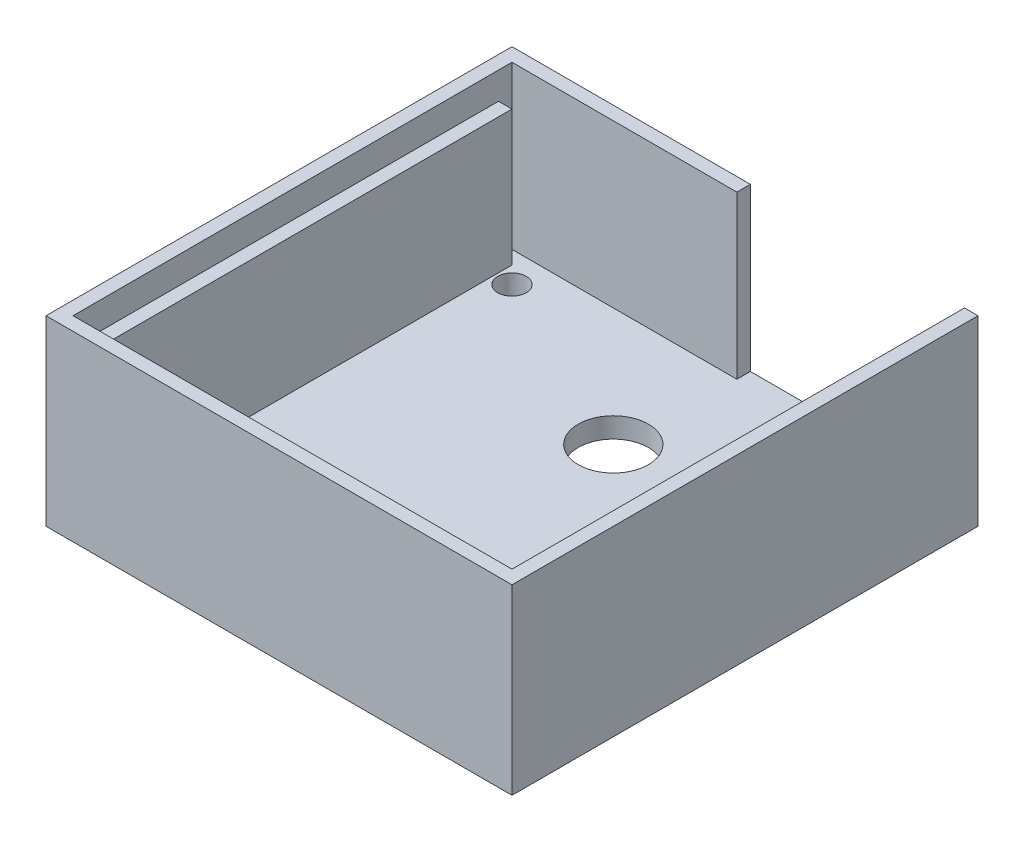
SolidWorks part; units mm, degrees
ref_plane "前视基准面" through (0, 0, 0) normal (0, 0, 1) x (1, 0, 0)
ref_plane "上视基准面" through (0, 0, 0) normal (0, 1, 0) x (1, 0, 0)
ref_plane "右视基准面" through (0, 0, 0) normal (1, 0, 0) x (0, 0, -1)
sketch "草图1" plane through (0, 0, 0) normal (0, 1, 0) x (1, 0, 0)
  line L1 (0, 0) -> (34.5, 0)
  line L2 (0, 0) -> (0, 34.5)
  line L3 (0, 34.5) -> (34.5, 34.5)
  line L4 (34.5, 0) -> (34.5, 34.5)
  dimension "D1" = 34.5
  dimension "D2" = 34.5
extrude "凸台-拉伸1" add sketch "草图1" along normal blind 13.5
sketch "草图2" plane through (0, 13.5, 0) normal (0, 1, 0) x (1, 0, 0)
  line L0 (17.25, 34.5) -> (17.25, -5.1184) construction
  line L1 (34.5, 34.5) -> (0, 34.5) construction
  line L2 (0, 17.25) -> (37.82, 17.25) construction
  line L3 (0, 34.5) -> (0, 0) construction
  line L16 (1, 33.5) -> (1, 1)
  line L17 (1, 1) -> (33.5, 1)
  line L18 (33.5, 1) -> (33.5, 33.5)
  line L19 (33.5, 33.5) -> (1, 33.5)
  dimension "D2" = 32.5
  dimension "D1" = 32.5
extrude "切除-拉伸1" cut sketch "草图2" against normal blind 2
sketch "草图3" plane through (0, 11.5, 0) normal (0, 1, 0) x (1, 0, 0)
  line L0 (17.25, 33.5) -> (17.25, 9.2832) construction
  line L1 (33.5, 33.5) -> (1, 33.5) construction
  line L2 (1, 17.25) -> (31.2686, 17.25) construction
  line L3 (1, 33.5) -> (1, 1) construction
  line L4 (33.5, 1) -> (33.5, 33.5) construction
  line L5 (2, 2) -> (32.5, 2)
  line L6 (2, 2) -> (2, 32.5)
  line L7 (2, 32.5) -> (32.5, 32.5)
  line L8 (32.5, 2) -> (32.5, 32.5)
  line L9 (2, 2) -> (32.5, 32.5) construction
  line L10 (2, 32.5) -> (32.5, 2) construction
  line L11 (33.5, 33.5) -> (1, 33.5) construction
  point P8 (17.25, 17.25)
  dimension "D1" = 1
  dimension "D2" = 1
extrude "切除-拉伸2" cut sketch "草图3" against normal offset from surface (10 mm away) 1.5 up to face at (17.25, 0, -17.25)
sketch "草图4" plane through (0, 1.5, 0) normal (0, 1, 0) x (1, 0, 0)
  line L0 (17.25, 32.5) -> (17.25, 2) construction
  line L1 (32.5, 32.5) -> (2, 32.5) construction
  line L2 (2, 2) -> (32.5, 2) construction
  line L3 (2, 17.25) -> (32.5, 17.25) construction
  line L4 (2, 32.5) -> (2, 2) construction
  line L5 (32.5, 2) -> (32.5, 32.5) construction
  circle A0 centre (3.25, 31.25) radius 1.0553
  circle A1 centre (31.25, 31.25) radius 1.0553
  circle A2 centre (31.25, 3.25) radius 1.0553
  circle A3 centre (3.25, 3.25) radius 1.0553
  circle A4 centre (17.25, 24.75) radius 2.6
  circle A5 centre (17.25, 9.75) radius 2.6
  dimension "D1" = 28
  dimension "D2" = 28
  dimension "D3" = 5.2
  dimension "D4" = 15
extrude "切除-拉伸3" cut sketch "草图4" against normal blind 12
sketch "草图5" plane through (0, 13.5, 0) normal (0, 1, 0) x (1, 0, 0)
  line L1 (17.65, 34.5) -> (33.5, 34.5)
  line L2 (17.65, 34.5) -> (17.65, 32.484)
  line L3 (17.65, 32.484) -> (33.5, 32.484)
  line L4 (33.5, 34.5) -> (33.5, 32.484)
  line L6 (33.5, 1) -> (33.5, 33.5) construction
  dimension "D1" = 15.85
extrude "切除-拉伸4" cut sketch "草图5" against normal up to surface (12 mm away) up to face at (31.25, 1.5, -32.3053)
sketch "草图7" plane through (0, 11.5, 0) normal (0, 1, 0) x (1, 0, 0)
  line L0 (1, 33.5) -> (1, 1) construction
  line L1 (17.65, 32.5) -> (1, 32.5)
  line L2 (17.65, 32.5) -> (17.65, 33.5)
  line L3 (17.65, 33.5) -> (1, 33.5)
  line L4 (1, 32.5) -> (1, 33.5)
  line L5 (1, 33.5) -> (1, 1) construction
extrude "切除-拉伸6" cut sketch "草图7" against normal blind 10
sketch "草图8" plane through (0, 11.5, 0) normal (0, 1, 0) x (1, 0, 0)
  line L0 (2, 2) -> (32.5, 2) construction
  line L1 (14.5, 2) -> (5, 2)
  line L2 (14.5, 2) -> (14.5, 1)
  line L3 (14.5, 1) -> (5, 1)
  line L4 (5, 2) -> (5, 1)
  line L5 (1, 1) -> (33.5, 1) construction
  line L6 (1, 32.5) -> (1, 1) construction
  dimension "D1" = 9.5
  dimension "D2" = 13.5
extrude "切除-拉伸7" cut sketch "草图8" against normal blind 10
